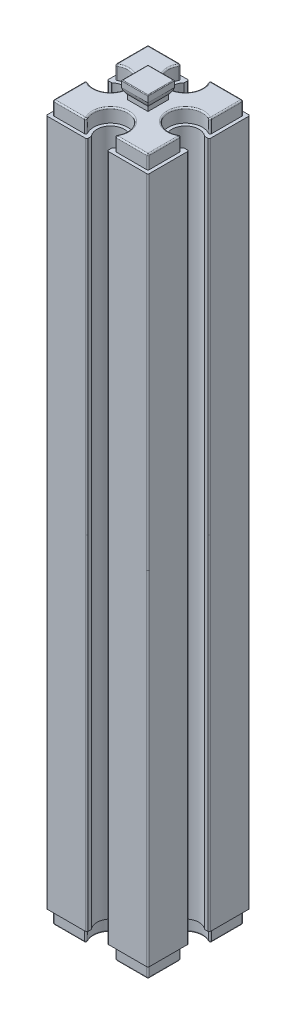
SolidWorks part; units mm, degrees
ref_plane "前视基准面" through (0, 0, 0) normal (0, 0, 1) x (1, 0, 0)
ref_plane "上视基准面" through (0, 0, 0) normal (0, 1, 0) x (1, 0, 0)
ref_plane "右视基准面" through (0, 0, 0) normal (1, 0, 0) x (0, 0, -1)
sketch "草图1" plane through (0, 0, 0) normal (0, 1, 0) x (1, 0, 0)
  line L0 (0, 0) -> (0, 7.5) construction
  line L1 (0, 0) -> (7.5, 0) construction
  line L2 (-7.5, 7.5) -> (-1.5, 7.5)
  line L3 (7.5, 7.5) -> (7.5, 1.5)
  line L4 (6.8229, 1.5) -> (7.5, 1.5)
  line L5 (6.8229, -1.5) -> (7.5, -1.5)
  line L6 (0, 7.5) -> (0, 5.5) construction
  line L7 (-1.5, 6.8229) -> (-1.5, 7.5)
  line L8 (1.5, 6.8229) -> (1.5, 7.5)
  line L9 (1.5, 7.5) -> (7.5, 7.5)
  line L10 (7.5, -1.5) -> (7.5, -7.5)
  line L11 (7.5, -7.5) -> (1.5, -7.5)
  line L12 (1.5, -6.8229) -> (1.5, -7.5)
  line L13 (-1.5, -6.8229) -> (-1.5, -7.5)
  line L14 (-1.5, -7.5) -> (-7.5, -7.5)
  line L15 (-7.5, -7.5) -> (-7.5, -1.5)
  line L16 (-6.8229, -1.5) -> (-7.5, -1.5)
  line L17 (-6.8229, 1.5) -> (-7.5, 1.5)
  line L18 (-7.5, 1.5) -> (-7.5, 7.5)
  arc A0 (-1.5, 6.8229) -> (1.5, 6.8229) centre (0, 5.5) ccw
  arc A1 (6.8229, 1.5) -> (6.8229, -1.5) centre (5.5, 0) ccw
  arc A2 (1.5, -6.8229) -> (-1.5, -6.8229) centre (0, -5.5) ccw
  arc A3 (-6.8229, -1.5) -> (-6.8229, 1.5) centre (-5.5, 0) ccw
  point P36 (0, 0)
  dimension "D6" = 4
  dimension "D7" = 2
  dimension "D1" = 7.5
  dimension "D2" = 7.5
  dimension "D3" = 2
  dimension "D4" = 7.5
  dimension "D5" = 1.5
extrude "凸台-拉伸1" add sketch "草图1" along normal blind 50.5
sketch "草图2" plane through (0, 50.5, 0) normal (0, 1, 0) x (1, 0, 0)
  line L0 (-7, 7) -> (-7, 2)
  line L1 (-7, 2) -> (-7, 2)
  line L2 (-7, -2) -> (-7, -2)
  line L3 (-7, -2) -> (-7, -7)
  line L4 (-7, -7) -> (-2, -7)
  line L5 (-2, -7) -> (-2, -7)
  line L6 (2, -7) -> (2, -7)
  line L7 (2, -7) -> (7, -7)
  line L8 (7, -7) -> (7, -2)
  line L9 (7, -2) -> (7, -2)
  line L10 (7, 2) -> (7, 2)
  line L11 (7, 2) -> (7, 7)
  line L12 (7, 7) -> (2, 7)
  line L13 (2, 7) -> (2, 7)
  line L14 (-2, 7) -> (-2, 7)
  line L15 (-2, 7) -> (-7, 7)
  line L16 (-7.5, 7.5) -> (-7.5, 1.5)
  line L17 (-7.5, 1.5) -> (-6.8229, 1.5)
  line L18 (-6.8229, -1.5) -> (-7.5, -1.5)
  line L19 (-7.5, -1.5) -> (-7.5, -7.5)
  line L20 (-7.5, -7.5) -> (-1.5, -7.5)
  line L21 (-1.5, -7.5) -> (-1.5, -6.8229)
  line L22 (1.5, -6.8229) -> (1.5, -7.5)
  line L23 (1.5, -7.5) -> (7.5, -7.5)
  line L24 (7.5, -7.5) -> (7.5, -1.5)
  line L25 (7.5, -1.5) -> (6.8229, -1.5)
  line L26 (6.8229, 1.5) -> (7.5, 1.5)
  line L27 (7.5, 1.5) -> (7.5, 7.5)
  line L28 (7.5, 7.5) -> (1.5, 7.5)
  line L29 (1.5, 7.5) -> (1.5, 6.8229)
  line L30 (-1.5, 6.8229) -> (-1.5, 7.5)
  line L31 (-1.5, 7.5) -> (-7.5, 7.5)
  line L32 (-7.5, 7.5) -> (-7.5, 1.5) construction
  line L33 (-7.5, 1.5) -> (-6.8229, 1.5) construction
  line L34 (-6.8229, -1.5) -> (-7.5, -1.5) construction
  line L35 (-7.5, -1.5) -> (-7.5, -7.5) construction
  line L36 (-7.5, -7.5) -> (-1.5, -7.5) construction
  line L37 (-1.5, -7.5) -> (-1.5, -6.8229) construction
  line L38 (1.5, -6.8229) -> (1.5, -7.5) construction
  line L39 (1.5, -7.5) -> (7.5, -7.5) construction
  line L40 (7.5, -7.5) -> (7.5, -1.5) construction
  line L41 (7.5, -1.5) -> (6.8229, -1.5) construction
  line L42 (6.8229, 1.5) -> (7.5, 1.5) construction
  line L43 (7.5, 1.5) -> (7.5, 7.5) construction
  line L44 (7.5, 7.5) -> (1.5, 7.5) construction
  line L45 (1.5, 7.5) -> (1.5, 6.8229) construction
  line L46 (-1.5, 6.8229) -> (-1.5, 7.5) construction
  line L47 (-1.5, 7.5) -> (-7.5, 7.5) construction
  arc A0 (-7, -2) -> (-7, 2) centre (-5.5, 0) ccw
  arc A1 (2, -7) -> (-2, -7) centre (0, -5.5) ccw
  arc A2 (7, 2) -> (7, -2) centre (5.5, 0) ccw
  arc A3 (-2, 7) -> (2, 7) centre (0, 5.5) ccw
  arc A4 (-6.8229, -1.5) -> (-6.8229, 1.5) centre (-5.5, 0) ccw
  arc A5 (1.5, -6.8229) -> (-1.5, -6.8229) centre (0, -5.5) ccw
  arc A6 (6.8229, 1.5) -> (6.8229, -1.5) centre (5.5, 0) ccw
  arc A7 (-1.5, 6.8229) -> (1.5, 6.8229) centre (0, 5.5) ccw
  arc A8 (-6.8229, -1.5) -> (-6.8229, 1.5) centre (-5.5, 0) ccw construction
  arc A9 (1.5, -6.8229) -> (-1.5, -6.8229) centre (0, -5.5) ccw construction
  arc A10 (6.8229, 1.5) -> (6.8229, -1.5) centre (5.5, 0) ccw construction
  arc A11 (-1.5, 6.8229) -> (1.5, 6.8229) centre (0, 5.5) ccw construction
  dimension "D1" = 0
  dimension "D2" = 0.5
extrude "凸台-拉伸2" add sketch "草图2" along normal blind 2
sketch "草图3" plane through (0, 0, 0) normal (1, 0, 0) x (0, 0, -1)
  line L0 (0, 52.5) -> (0, 54.5) construction
  line L1 (2.5, 52.5) -> (-2.5, 52.5) construction
  line L2 (0, 54.5) -> (0, 55) construction
  line L3 (-1.5, 52.5) -> (1.5, 52.5)
  line L4 (1.5, 52.5) -> (1.5, 53.1771)
  line L5 (-1.95, 55) -> (1.95, 55)
  line L6 (1.95, 55) -> (1.95, 54.0556)
  line L7 (-1.5, 52.5) -> (-1.5, 53.1771)
  line L8 (-1.95, 55) -> (-1.95, 54.0556)
  arc A0 (-1.5, 53.1771) -> (-1.95, 54.0556) centre (0, 54.5) cw
  arc A1 (1.5, 53.1771) -> (1.95, 54.0556) centre (0, 54.5) ccw
  dimension "D5" = 2
  dimension "D1" = 2
  dimension "D2" = 0.5
  dimension "D3" = 1.5
  dimension "D4" = 1.95
extrude "凸台-拉伸3" add sketch "草图3" along normal blind 2 and the other way blind 2
sketch "草图4" plane through (0, 0, 0) normal (0, 0, 1) x (1, 0, 0)
  line L0 (0, 52.5) -> (0, 54.5) construction
  line L2 (-2, 52.5) -> (2, 52.5) construction
  line L3 (0, 54.5) -> (0, 55) construction
  line L4 (-2, 55) -> (2, 55) construction
  line L5 (1.95, 55) -> (2, 55)
  line L6 (-1.95, 55) -> (-1.95, 54.0556)
  line L9 (-1.5, 52.5) -> (-1.5, 53.1771)
  line L10 (1.5, 52.5) -> (1.5, 53.1771)
  line L11 (1.95, 55) -> (1.95, 54.0556)
  line L12 (1.5, 52.5) -> (2, 52.5)
  line L13 (-2, 55) -> (-1.95, 55)
  line L14 (-2, 55) -> (-2, 52.5)
  line L15 (-2, 52.5) -> (-1.5, 52.5)
  line L16 (2, 55) -> (2, 52.5)
  arc A0 (-1.95, 54.0556) -> (-1.5, 53.1771) centre (0, 54.5) ccw
  arc A1 (1.95, 54.0556) -> (1.5, 53.1771) centre (0, 54.5) cw
  dimension "D1" = 2
  dimension "D2" = 1.5
  dimension "D3" = 1.95
fillet "圆角3" radius 0.2 13 edges at (-1.5, 25.25, -7.5) (1.5, 25.25, -7.5) (7.5, 25.25, -7.5) (7.5, 25.25, -1.5) (7.5, 25.25, 1.5) (7.5, 25.25, 7.5) (-1.5, 25.25, 7.5) (1.5, 25.25, 7.5) (-6.8229, 25.25, -1.5) (-7.5, 25.25, 7.5) (-7.5, 25.25, 1.5) (-7.5, 25.25, -1.5) (-7.5, 25.25, -7.5)
extrude "切除-拉伸1" cut sketch "草图4" against normal blind 3 and the other way blind 3
fillet "圆角4" radius 0.2 24 edges at (0, 52.5, 3) (-3, 52.5, 0) (0, 52.5, -3) (3, 52.5, 0) (7, 51.5, 2) (7, 51.5, -2) (2, 51.5, -7) (-2, 51.5, -7) (-7, 51.5, 2) (-7, 51.5, -2) (2, 51.5, 7) (-2, 51.5, 7) (7, 51.5, 7) (4.5, 52.5, 7) (7, 52.5, 4.5) (7, 52.5, -4.5) (7, 51.5, -7) (4.5, 52.5, -7) (-4.5, 52.5, -7) (-7, 51.5, -7) (-7, 52.5, -4.5) (-4.5, 52.5, 7) (-7, 52.5, 4.5) (-7, 51.5, 7)
fillet "圆角5" radius 0.1 4 edges at (0, 55, -1.95) (1.95, 55, 0) (0, 55, 1.95) (-1.95, 55, 0)
mirror "镜向1" of "圆角5", "圆角4", "切除-拉伸1", "圆角3", "凸台-拉伸3", "凸台-拉伸2", "凸台-拉伸1"
